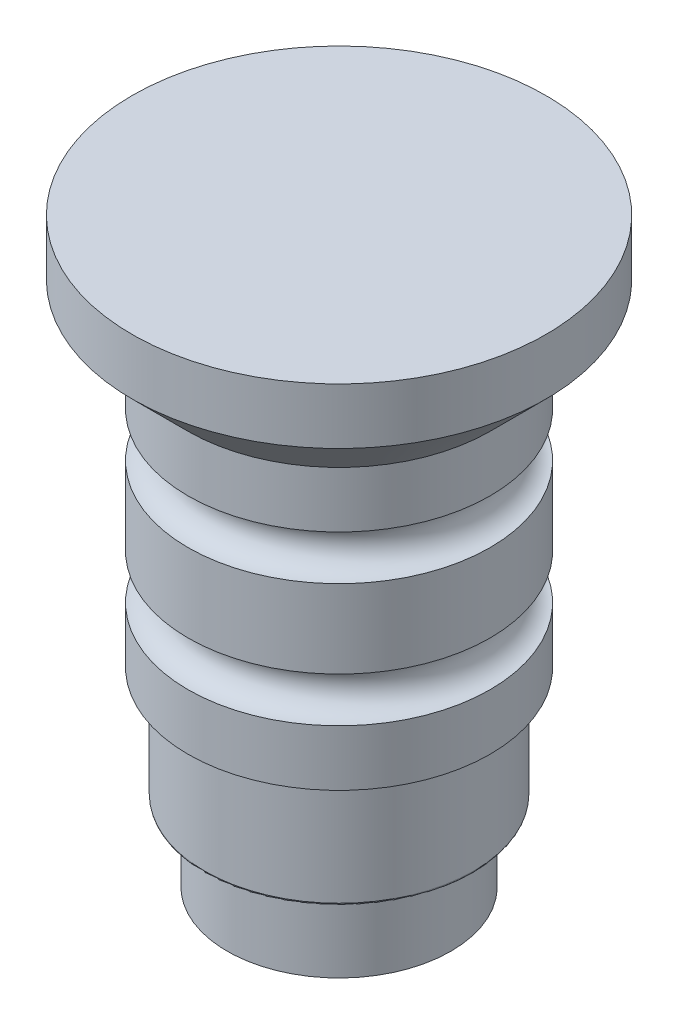
SolidWorks part; units mm, degrees
ref_plane "Plan de face" through (0, 0, 0) normal (0, 0, 1) x (1, 0, 0)
ref_plane "Plan de dessus" through (0, 0, 0) normal (0, 1, 0) x (1, 0, 0)
ref_plane "Plan de droite" through (0, 0, 0) normal (1, 0, 0) x (0, 0, -1)
sketch "Esquisse1" plane through (0, 0, 0) normal (0, 0, 1) x (1, 0, 0)
  line L1 (0, 0) -> (-7.5, 0) construction
  line L3 (-7.5, 0) -> (-10, 0)
  line L4 (-10, 0) -> (-10, 7)
  line L5 (-10, 7) -> (-12, 7)
  line L6 (-12, 7) -> (-12, 17)
  line L7 (-12, 17) -> (-13.5, 17)
  line L8 (-13.5, 17) -> (-13.5, 22)
  line L9 (-13.5, 26) -> (-13.5, 33)
  line L10 (-13.5, 37) -> (-13.5, 42)
  line L11 (-13.5, 42) -> (0, 42) construction
  line L12 (0, 42) -> (0, 0) construction
  line L20 (-13.5, 42) -> (0, 42) construction
  line L21 (-13.5, 42) -> (-18.5, 47)
  line L22 (-18.5, 47) -> (-18.5, 52)
  line L23 (-18.5, 52) -> (0, 52)
  line L24 (0, 52) -> (0, 42)
  line L25 (-7.5, 0) -> (-7.5, 12)
  line L26 (-7.5, 12) -> (0, 12)
  line L27 (0, 12) -> (0, 42)
  arc A0 (-13.5, 37) -> (-13.5, 33) centre (-13.5, 35) cw
  arc A1 (-13.5, 26) -> (-13.5, 22) centre (-13.5, 24) cw
  dimension "D1" = 2
  dimension "D2" = 7
  dimension "D3" = 5
  dimension "D4" = 5
  dimension "D5" = 12
  dimension "D6" = 13.5
  dimension "D7" = 7
  dimension "D8" = 2.5
  dimension "D9" = 7.5
  dimension "D10" = 17
  dimension "D11" = 5
  dimension "D12" = 5
  dimension "D13" = 135
  dimension "D14" = 12
revolve "Révolution1" add sketch "Esquisse1" angle 360 about L12
fillet "Congé3" radius 0.2 2 edges at (-10, 7, 0) (-12, 7, 0)
